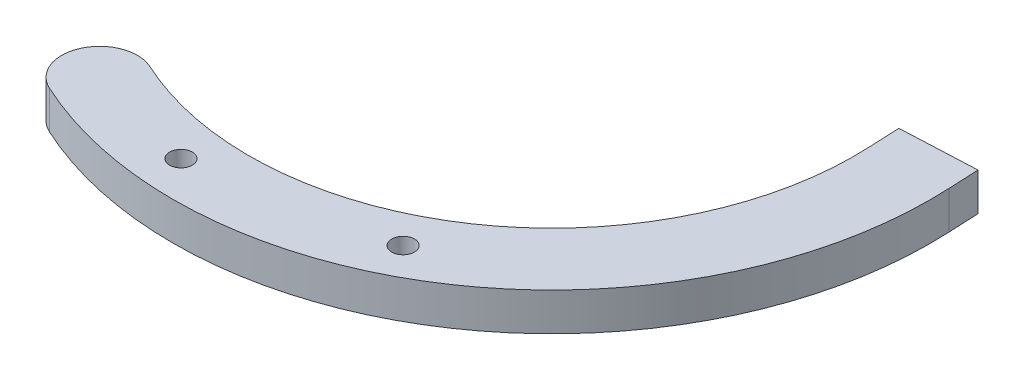
SolidWorks part; units mm, degrees
ref_plane "前视基准面" through (0, 0, 0) normal (0, 0, 1) x (1, 0, 0)
ref_plane "上视基准面" through (0, 0, 0) normal (0, 1, 0) x (1, 0, 0)
ref_plane "右视基准面" through (0, 0, 0) normal (1, 0, 0) x (0, 0, -1)
sketch "草图1" plane through (0, 0, 0) normal (0, 1, 0) x (1, 0, 0)
  line L1 (61.0237, 33.5692) -> (61.022, 33.6048)
  line L2 (61.0237, 33.5692) -> (60.8371, 37.6006)
  line L3 (71.0113, 34.0674) -> (70.8263, 38.0631)
  line L224 (70.8263, 38.0631) -> (60.8371, 37.6006)
  arc A1 (4.3466, -4.7583) -> (61.0237, 33.5692) centre (21.0734, 31.5765) ccw
  arc A33 (4.3466, -4.7583) -> (0.1649, -13.842) centre (2.2558, -9.3001) ccw
  arc A134 (0.1649, -13.842) -> (71.0113, 34.0674) centre (21.0734, 31.5765) ccw
  point P17 (22.7627, 23.6193)
  point P31 (21.9431, -11.3711)
  point P47 (55.4539, 11.1181)
extrude "凸台-拉伸1" add sketch "草图1" along normal blind 5
sketch "草图2" plane through (0, 5, 0) normal (0, 1, 0) x (1, 0, 0)
  circle A0 centre (16.9304, -13.2324) radius 1.5
  circle A1 centre (41.5228, -8.5087) radius 1.5
extrude "切除-拉伸1" cut sketch "草图2" against normal up to next
